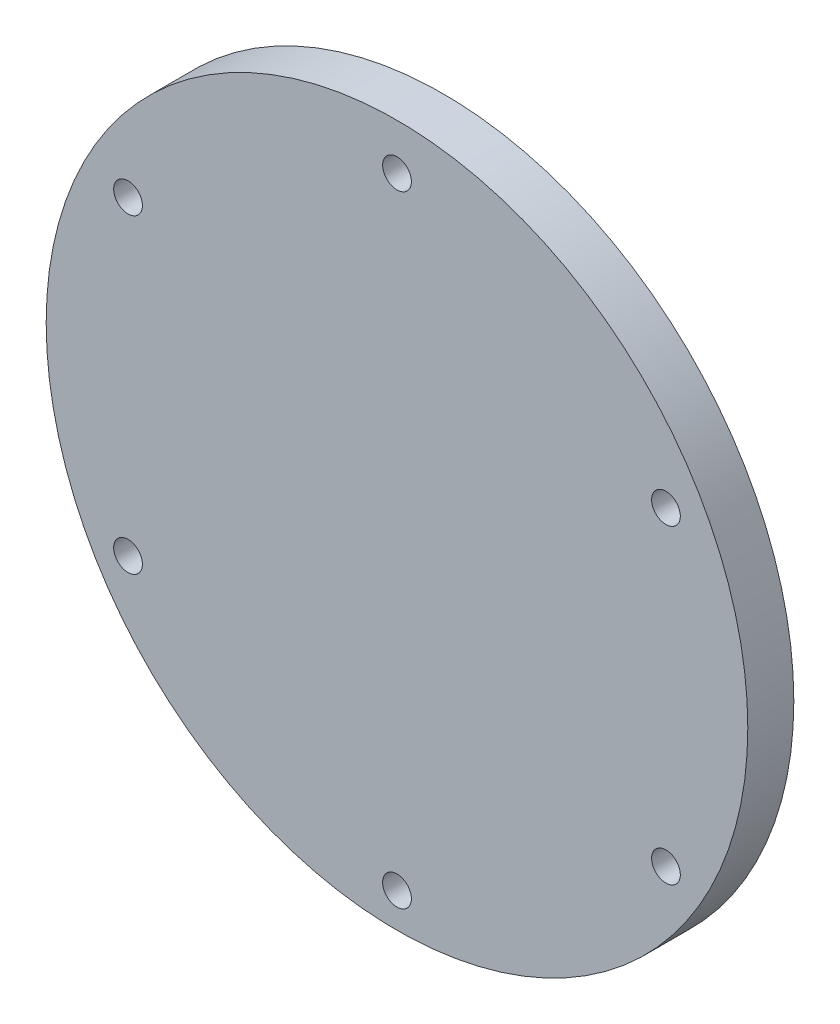
SolidWorks part; units mm, degrees
ref_plane "Front Plane" through (0, 0, 0) normal (0, 0, 1) x (1, 0, 0)
ref_plane "Top Plane" through (0, 0, 0) normal (0, 1, 0) x (1, 0, 0)
ref_plane "Right Plane" through (0, 0, 0) normal (1, 0, 0) x (0, 0, -1)
sketch "Sketch1" plane through (0, 0, 0) normal (0, 0, 1) x (-1, 0, 0)
  line L0 (0, -1) -> (0, 54) construction
  circle A0 centre (0, 54) radius 2.5
  circle A2 centre (0, -1) radius 61
  circle A3 centre (46.7654, 27) radius 2.5
  circle A4 centre (46.7654, -27) radius 2.5
  circle A5 centre (0, -54) radius 2.5
  circle A6 centre (-46.7654, -27) radius 2.5
  circle A7 centre (-46.7654, 27) radius 2.5
  point P18 (0, 0)
  dimension "D2" = 6
extrude "Boss-Extrude1" add sketch "Sketch1" along normal blind 8
